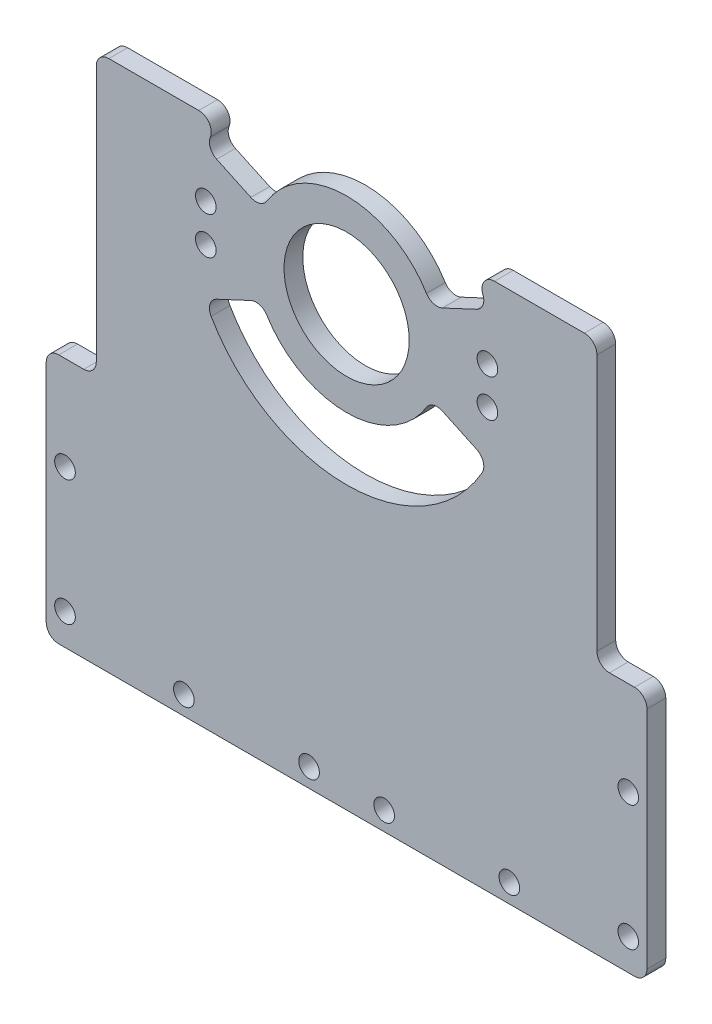
SolidWorks part; units mm, degrees
material "玻纤板"
ref_plane "前视基准面" through (0, 0, 0) normal (0, 0, 1) x (1, 0, 0)
ref_plane "上视基准面" through (0, 0, 0) normal (0, 1, 0) x (1, 0, 0)
ref_plane "右视基准面" through (0, 0, 0) normal (1, 0, 0) x (0, 0, -1)
other "Configuration Table"
sketch "草图1" plane through (0, 0, 0) normal (0, 0, 1) x (1, 0, 0)
  line L0 (0, 27.5) -> (0, -41.2576) construction
  line L1 (-40, 42.5) -> (40, 42.5)
  line L2 (-40, 42.5) -> (-40, -42.5)
  line L3 (-40, -42.5) -> (40, -42.5)
  line L4 (40, 42.5) -> (40, -42.5)
  line L5 (-40, 42.5) -> (40, -42.5) construction
  line L6 (-40, -42.5) -> (40, 42.5) construction
  line L7 (0, 27.5) -> (-56.2389, 27.5) construction
  circle A0 centre (0, 27.5) radius 10
  circle A1 centre (-6, -39.5) radius 1.65
  circle A2 centre (-26, -39.5) radius 1.65
  circle A3 centre (26, -39.5) radius 1.65
  circle A4 centre (6, -39.5) radius 1.65
  circle A5 centre (-22.5, 30.5) radius 1.65
  circle A6 centre (-22.5, 24.5) radius 1.65
  circle A7 centre (22.5, 30.5) radius 1.65
  circle A8 centre (22.5, 24.5) radius 1.65
  point P25 (0, 0)
  dimension "D1" = 20
  dimension "D2" = 3
  dimension "D3" = 3.3
  dimension "D4" = 20
  dimension "D5" = 12
  dimension "D8" = 3.3
  dimension "D9" = 45
  dimension "D10" = 70
  dimension "D6" = 80
  dimension "D7" = 6
  dimension "D11" = 85
extrude "凸台-拉伸1" add sketch "草图1" along normal blind 3
sketch "草图2" plane through (0, 0, 3) normal (0, 0, 1) x (1, 0, 0)
  line L0 (0, 27.5) -> (61.7399, 27.5) construction
  line L1 (22.6577, 16.9345) -> (13.5946, 21.1607)
  line L2 (0, 0) -> (0, 47.0881) construction
  line L3 (-22.6577, 16.9345) -> (-13.5946, 21.1607)
  line L4 (-22.6577, 38.0655) -> (-13.5946, 33.8393)
  line L5 (22.6577, 38.0655) -> (13.5946, 33.8393)
  arc A0 (-13.5946, 21.1607) -> (13.5946, 21.1607) centre (0, 27.5) ccw
  arc A1 (-22.6577, 16.9345) -> (22.6577, 16.9345) centre (0, 27.5) ccw
  arc A2 (-22.6577, 38.0655) -> (22.6577, 38.0655) centre (0, 27.5) cw
  arc A3 (-13.5946, 33.8393) -> (13.5946, 33.8393) centre (0, 27.5) cw
  dimension "D1" = 15
  dimension "D2" = 25
  dimension "D3" = 130
extrude "切除-拉伸1" cut sketch "草图2" against normal through all
sketch "草图3" plane through (0, 0, 3) normal (0, 0, 1) x (1, 0, 0)
  line L0 (0, -42.5) -> (0, 62.8928) construction
  line L1 (40, -42.5) -> (48, -42.5)
  line L2 (40, -42.5) -> (40, -2.5)
  line L3 (40, -2.5) -> (48, -2.5)
  line L4 (48, -42.5) -> (48, -2.5)
  line L5 (-40, -42.5) -> (40, -42.5) construction
  line L6 (-48, -42.5) -> (-48, -2.5)
  line L7 (-40, -2.5) -> (-48, -2.5)
  line L8 (-40, -42.5) -> (-40, -2.5)
  line L9 (-40, -42.5) -> (-48, -42.5)
  dimension "D1" = 8
  dimension "D2" = 40
extrude "凸台-拉伸2" add sketch "草图3" against normal blind 3
sketch "草图4" plane through (0, 0, 3) normal (0, 0, 1) x (1, 0, 0)
  line L0 (-48, -42.5) -> (48, -42.5) construction
  line L1 (48, -42.5) -> (48, -2.5) construction
  line L2 (0, -42.5) -> (0, 57.9613) construction
  circle A0 centre (45, -37.5) radius 1.65
  circle A1 centre (45, -17.5) radius 1.65
  circle A2 centre (-45, -17.5) radius 1.65
  circle A3 centre (-45, -37.5) radius 1.65
  dimension "D1" = 3.3
  dimension "D4" = 20
  dimension "D2" = 5
  dimension "D3" = 3
extrude "切除-拉伸2" cut sketch "草图4" against normal through all
fillet "圆角1" radius 2 12 edges at (-40, 42.5, 1.5) (22.6577, 16.9345, 1.5) (-22.6577, 16.9345, 1.5) (13.5946, 21.1607, 1.5) (-13.5946, 21.1607, 1.5) (-22.6577, 38.0655, 1.5) (-13.5946, 33.8393, 1.5) (13.5946, 33.8393, 1.5) (22.6577, 38.0655, 1.5) (-48, -2.5, 1.5) (40, -2.5, 1.5) (48, -2.5, 1.5)
fillet "圆角2" radius 2 6 edges at (20, 42.5, 1.5) (-20, 42.5, 1.5) (40, 42.5, 1.5) (-48, -42.5, 1.5) (48, -42.5, 1.5) (-40, -2.5, 1.5)
